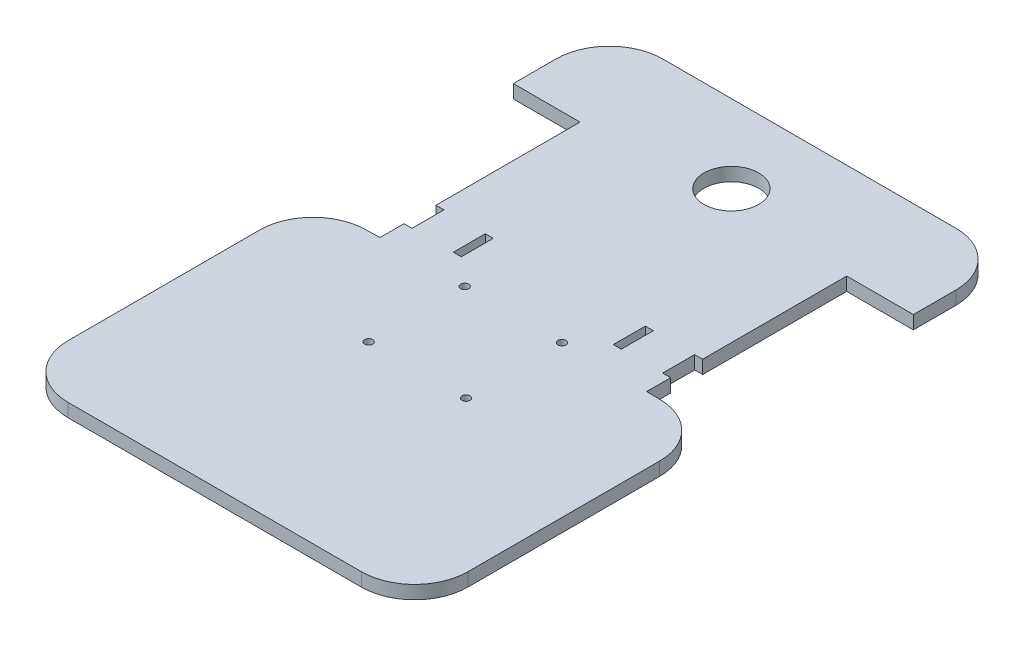
SolidWorks part; units mm, degrees
ref_plane "Front Plane" through (0, 0, 0) normal (0, 0, 1) x (1, 0, 0)
ref_plane "Top Plane" through (0, 0, 0) normal (0, 1, 0) x (1, 0, 0)
ref_plane "Right Plane" through (0, 0, 0) normal (1, 0, 0) x (0, 0, -1)
sketch "Sketch1" plane through (0, 0, 0) normal (0, 1, 0) x (1, 0, 0)
  line L0 (75, 0) -> (75, 223)
  line L5 (0, 0) -> (150, 0)
  line L6 (0, 0) -> (0, 223)
  line L7 (0, 223) -> (150, 223)
  line L8 (150, 0) -> (150, 223)
  line L9 (0, 223) -> (25, 223)
  line L10 (75, 112) -> (93.25, 112)
  line L11 (25, 187) -> (0, 187)
  line L12 (25, 187) -> (25, 112)
  line L13 (25, 112) -> (0, 111.5)
  line L14 (25, 112) -> (25, 120.9914)
  line L15 (25, 120.9914) -> (28, 120.9914)
  line L16 (28, 120.9914) -> (28, 132.9914)
  line L17 (28, 132.9914) -> (25, 132.9914)
  line L18 (43.5, 132.9914) -> (46.5, 132.9914)
  line L19 (46.5, 132.9914) -> (46.5, 120.9914)
  line L20 (46.5, 120.9914) -> (43.5, 120.9914)
  line L21 (43.5, 120.9914) -> (43.5, 132.9914)
  line L22 (106.5, 120.9914) -> (106.5, 132.9914)
  line L23 (103.5, 120.9914) -> (106.5, 120.9914)
  line L24 (103.5, 132.9914) -> (103.5, 120.9914)
  line L25 (106.5, 132.9914) -> (103.5, 132.9914)
  line L26 (122, 120.9914) -> (122, 132.9914)
  line L27 (125, 120.9914) -> (122, 120.9914)
  line L28 (122, 132.9914) -> (125, 132.9914)
  line L29 (125, 112) -> (150, 111.5)
  line L30 (125, 187) -> (125, 112)
  line L31 (125, 187) -> (150, 187)
  line L32 (75, 112) -> (56.75, 112)
  line L33 (56.75, 112) -> (56.75, 76)
  line L34 (56.75, 76) -> (93.25, 76)
  line L35 (93.25, 76) -> (93.25, 112)
  circle A0 centre (75, 193.7449) radius 10.25
  circle A1 centre (56.75, 112) radius 1.5
  circle A2 centre (56.75, 76) radius 1.5
  circle A3 centre (93.25, 76) radius 1.5
  circle A4 centre (93.25, 112) radius 1.5
extrude "Boss-Extrude1" add sketch "Sketch1" along normal blind 5 contours A2 L33 A1 L32 L0 A0 L7 L6 L11 L12 L17 L16 L15 L13 L5 L34 L20 L21 L18 L19 | A4 L35 A3 L34 L0 L5 L8 L29 L30 L27 L26 L28 L31 L7 A0 L10 L25 L22 L23 L24 | A4 L10 L0 L34 A3 L35 | A2 L34 L0 L32 A1 L33
fillet "Fillet3" radius 20 1 edges at (0, 2.5, -223)
fillet "Fillet4" radius 20 1 edges at (150, 2.5, -223)
fillet "Fillet5" radius 20 4 edges at (150, 2.5, -111.5) (150, 2.5, 0) (0, 2.5, 0) (0, 2.5, -111.5)
